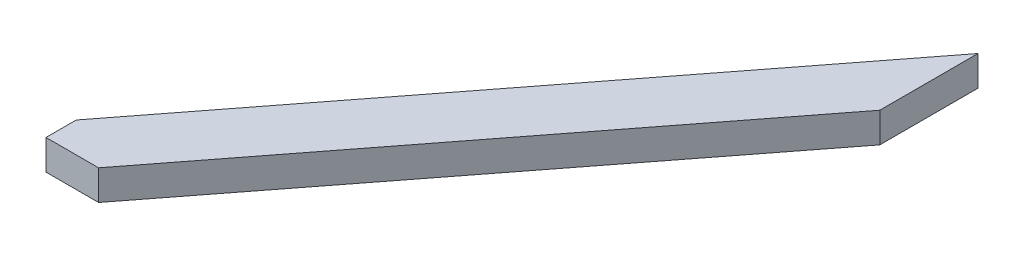
SolidWorks part; units mm, degrees
material "Pine"
ref_plane "Front Plane" through (0, 0, 0) normal (0, 0, 1) x (1, 0, 0)
ref_plane "Top Plane" through (0, 0, 0) normal (0, 1, 0) x (1, 0, 0)
ref_plane "Right Plane" through (0, 0, 0) normal (1, 0, 0) x (0, 0, -1)
sketch "Sketch2" plane through (0, 710.7, 0) normal (0, -1, 0) x (1, 0, 0)
  line L0 (665, 1298.9403) -> (0, 2158.673)
  line L2 (0, 2209.8) -> (88.9, 2209.8)
  line L3 (88.9, 2209.8) -> (665, 1465)
  line L8 (665, 1465) -> (665, 1298.9403)
  line L9 (665, 127.5) -> (665, 2002.5) construction
  line L10 (2286, 1465) -> (0, 1465) construction
  line L11 (0, 2209.8) -> (0, 2158.673)
  line L12 (0, 2247.9) -> (0, -38.1) construction
  dimension "D1" = 101.6
extrude "Boss-Extrude1" add sketch "Sketch2" along normal blind 50.8
